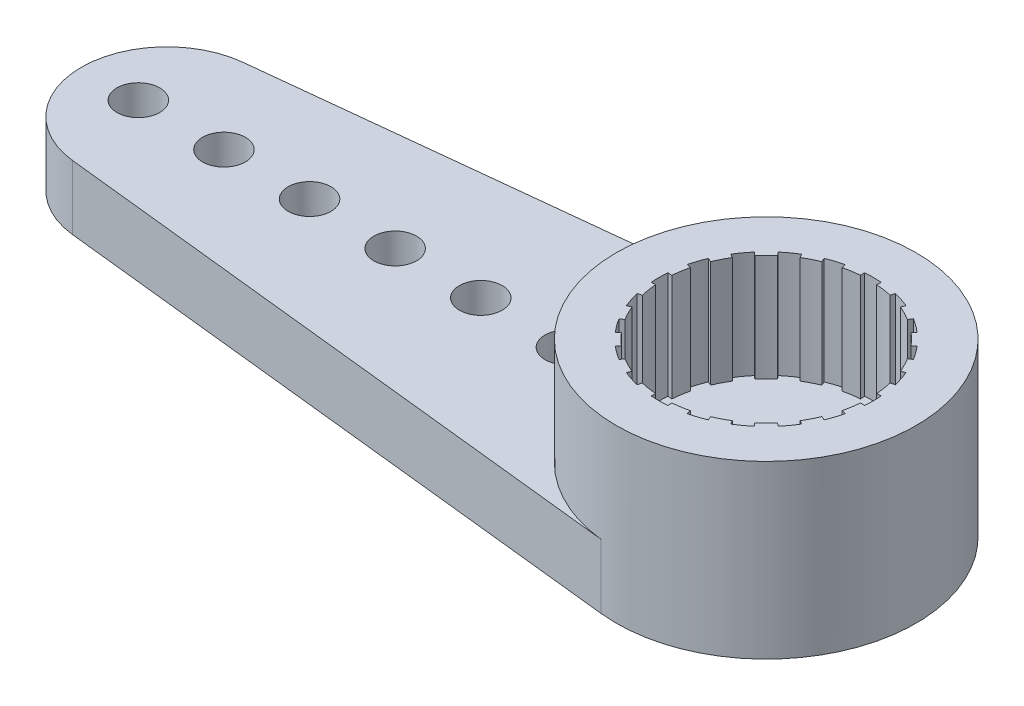
SolidWorks part; units mm, degrees
ref_plane "Front Plane" through (0, 0, 0) normal (0, 0, 1) x (1, 0, 0)
ref_plane "Top Plane" through (0, 0, 0) normal (0, 1, 0) x (1, 0, 0)
ref_plane "Right Plane" through (0, 0, 0) normal (1, 0, 0) x (0, 0, -1)
sketch "Sketch1" plane through (0, 0, 0) normal (0, 1, 0) x (1, 0, 0)
  line L0 (0, 0) -> (2.5, 0) construction
  line L1 (0, 0) -> (2.3705, 0.3754) construction
  line L2 (0, 0) -> (2.4923, 0.1961) construction
  line L3 (2.3926, 0.1883) -> (2.4923, 0.1961)
  line L4 (2.3926, -0.1883) -> (2.4923, -0.1961)
  line L5 (2.3337, -0.5603) -> (2.4309, -0.5836)
  line L6 (2.2173, -0.9184) -> (2.3097, -0.9567)
  line L7 (2.0463, -1.254) -> (2.1316, -1.3062)
  line L8 (1.825, -1.5587) -> (1.901, -1.6236)
  line L9 (1.5587, -1.825) -> (1.6236, -1.901)
  line L10 (1.254, -2.0463) -> (1.3062, -2.1316)
  line L11 (0.9184, -2.2173) -> (0.9567, -2.3097)
  line L12 (0.5603, -2.3337) -> (0.5836, -2.4309)
  line L13 (0.1883, -2.3926) -> (0.1961, -2.4923)
  line L14 (-0.1883, -2.3926) -> (-0.1961, -2.4923)
  line L15 (-0.5603, -2.3337) -> (-0.5836, -2.4309)
  line L16 (-0.9184, -2.2173) -> (-0.9567, -2.3097)
  line L17 (-1.254, -2.0463) -> (-1.3062, -2.1316)
  line L18 (-1.5587, -1.825) -> (-1.6236, -1.901)
  line L19 (-1.825, -1.5587) -> (-1.901, -1.6236)
  line L20 (-2.0463, -1.254) -> (-2.1316, -1.3062)
  line L21 (-2.2173, -0.9184) -> (-2.3097, -0.9567)
  line L22 (-2.3337, -0.5603) -> (-2.4309, -0.5836)
  line L23 (-2.3926, -0.1883) -> (-2.4923, -0.1961)
  line L24 (-2.3926, 0.1883) -> (-2.4923, 0.1961)
  line L25 (-2.3337, 0.5603) -> (-2.4309, 0.5836)
  line L26 (-2.2173, 0.9184) -> (-2.3097, 0.9567)
  line L27 (-2.0463, 1.254) -> (-2.1316, 1.3062)
  line L28 (-1.825, 1.5587) -> (-1.901, 1.6236)
  line L29 (-1.5587, 1.825) -> (-1.6236, 1.901)
  line L30 (-1.254, 2.0463) -> (-1.3062, 2.1316)
  line L31 (-0.9184, 2.2173) -> (-0.9567, 2.3097)
  line L32 (-0.5603, 2.3337) -> (-0.5836, 2.4309)
  line L33 (-0.1883, 2.3926) -> (-0.1961, 2.4923)
  line L34 (0.1883, 2.3926) -> (0.1961, 2.4923)
  line L35 (0.5603, 2.3337) -> (0.5836, 2.4309)
  line L36 (0.9184, 2.2173) -> (0.9567, 2.3097)
  line L37 (1.254, 2.0463) -> (1.3062, 2.1316)
  line L38 (1.5587, 1.825) -> (1.6236, 1.901)
  line L39 (1.825, 1.5587) -> (1.901, 1.6236)
  line L40 (2.0463, 1.254) -> (2.1316, 1.3062)
  line L41 (2.2173, 0.9184) -> (2.3097, 0.9567)
  line L42 (2.3337, 0.5603) -> (2.4309, 0.5836)
  circle A0 centre (0, 0) radius 2.5 construction
  circle A1 centre (0, 0) radius 2.4 construction
  circle A2 centre (0, 0) radius 3.5
  arc A3 (2.3705, 0.3754) -> (2.3926, 0.1883) centre (0, 0) cw
  arc A4 (2.4923, 0.1961) -> (2.4923, -0.1961) centre (0, 0) cw
  arc A5 (2.3705, -0.3754) -> (2.3926, -0.1883) centre (0, 0) ccw
  arc A6 (2.3705, -0.3754) -> (2.3337, -0.5603) centre (0, 0) cw
  arc A7 (2.4309, -0.5836) -> (2.3097, -0.9567) centre (0, 0) cw
  arc A8 (2.1384, -1.0896) -> (2.2173, -0.9184) centre (0, 0) ccw
  arc A9 (2.1384, -1.0896) -> (2.0463, -1.254) centre (0, 0) cw
  arc A10 (2.1316, -1.3062) -> (1.901, -1.6236) centre (0, 0) cw
  arc A11 (1.6971, -1.6971) -> (1.825, -1.5587) centre (0, 0) ccw
  arc A12 (1.6971, -1.6971) -> (1.5587, -1.825) centre (0, 0) cw
  arc A13 (1.6236, -1.901) -> (1.3062, -2.1316) centre (0, 0) cw
  arc A14 (1.0896, -2.1384) -> (1.254, -2.0463) centre (0, 0) ccw
  arc A15 (1.0896, -2.1384) -> (0.9184, -2.2173) centre (0, 0) cw
  arc A16 (0.9567, -2.3097) -> (0.5836, -2.4309) centre (0, 0) cw
  arc A17 (0.3754, -2.3705) -> (0.5603, -2.3337) centre (0, 0) ccw
  arc A18 (0.3754, -2.3705) -> (0.1883, -2.3926) centre (0, 0) cw
  arc A19 (0.1961, -2.4923) -> (-0.1961, -2.4923) centre (0, 0) cw
  arc A20 (-0.3754, -2.3705) -> (-0.1883, -2.3926) centre (0, 0) ccw
  arc A21 (-0.3754, -2.3705) -> (-0.5603, -2.3337) centre (0, 0) cw
  arc A22 (-0.5836, -2.4309) -> (-0.9567, -2.3097) centre (0, 0) cw
  arc A23 (-1.0896, -2.1384) -> (-0.9184, -2.2173) centre (0, 0) ccw
  arc A24 (-1.0896, -2.1384) -> (-1.254, -2.0463) centre (0, 0) cw
  arc A25 (-1.3062, -2.1316) -> (-1.6236, -1.901) centre (0, 0) cw
  arc A26 (-1.6971, -1.6971) -> (-1.5587, -1.825) centre (0, 0) ccw
  arc A27 (-1.6971, -1.6971) -> (-1.825, -1.5587) centre (0, 0) cw
  arc A28 (-1.901, -1.6236) -> (-2.1316, -1.3062) centre (0, 0) cw
  arc A29 (-2.1384, -1.0896) -> (-2.0463, -1.254) centre (0, 0) ccw
  arc A30 (-2.1384, -1.0896) -> (-2.2173, -0.9184) centre (0, 0) cw
  arc A31 (-2.3097, -0.9567) -> (-2.4309, -0.5836) centre (0, 0) cw
  arc A32 (-2.3705, -0.3754) -> (-2.3337, -0.5603) centre (0, 0) ccw
  arc A33 (-2.3705, -0.3754) -> (-2.3926, -0.1883) centre (0, 0) cw
  arc A34 (-2.4923, -0.1961) -> (-2.4923, 0.1961) centre (0, 0) cw
  arc A35 (-2.3705, 0.3754) -> (-2.3926, 0.1883) centre (0, 0) ccw
  arc A36 (-2.3705, 0.3754) -> (-2.3337, 0.5603) centre (0, 0) cw
  arc A37 (-2.4309, 0.5836) -> (-2.3097, 0.9567) centre (0, 0) cw
  arc A38 (-2.1384, 1.0896) -> (-2.2173, 0.9184) centre (0, 0) ccw
  arc A39 (-2.1384, 1.0896) -> (-2.0463, 1.254) centre (0, 0) cw
  arc A40 (-2.1316, 1.3062) -> (-1.901, 1.6236) centre (0, 0) cw
  arc A41 (-1.6971, 1.6971) -> (-1.825, 1.5587) centre (0, 0) ccw
  arc A42 (-1.6971, 1.6971) -> (-1.5587, 1.825) centre (0, 0) cw
  arc A43 (-1.6236, 1.901) -> (-1.3062, 2.1316) centre (0, 0) cw
  arc A44 (-1.0896, 2.1384) -> (-1.254, 2.0463) centre (0, 0) ccw
  arc A45 (-1.0896, 2.1384) -> (-0.9184, 2.2173) centre (0, 0) cw
  arc A46 (-0.9567, 2.3097) -> (-0.5836, 2.4309) centre (0, 0) cw
  arc A47 (-0.3754, 2.3705) -> (-0.5603, 2.3337) centre (0, 0) ccw
  arc A48 (-0.3754, 2.3705) -> (-0.1883, 2.3926) centre (0, 0) cw
  arc A49 (-0.1961, 2.4923) -> (0.1961, 2.4923) centre (0, 0) cw
  arc A50 (0.3754, 2.3705) -> (0.1883, 2.3926) centre (0, 0) ccw
  arc A51 (0.3754, 2.3705) -> (0.5603, 2.3337) centre (0, 0) cw
  arc A52 (0.5836, 2.4309) -> (0.9567, 2.3097) centre (0, 0) cw
  arc A53 (1.0896, 2.1384) -> (0.9184, 2.2173) centre (0, 0) ccw
  arc A54 (1.0896, 2.1384) -> (1.254, 2.0463) centre (0, 0) cw
  arc A55 (1.3062, 2.1316) -> (1.6236, 1.901) centre (0, 0) cw
  arc A56 (1.6971, 1.6971) -> (1.5587, 1.825) centre (0, 0) ccw
  arc A57 (1.6971, 1.6971) -> (1.825, 1.5587) centre (0, 0) cw
  arc A58 (1.901, 1.6236) -> (2.1316, 1.3062) centre (0, 0) cw
  arc A59 (2.1384, 1.0896) -> (2.0463, 1.254) centre (0, 0) ccw
  arc A60 (2.1384, 1.0896) -> (2.2173, 0.9184) centre (0, 0) cw
  arc A61 (2.3097, 0.9567) -> (2.4309, 0.5836) centre (0, 0) cw
  arc A62 (2.3705, 0.3754) -> (2.3337, 0.5603) centre (0, 0) ccw
  point P130 (0, 0)
  dimension "D1" = 5
  dimension "D2" = 4.8
  dimension "D3" = 7
  dimension "D4" = 9
  dimension "D5" = 4.5
  dimension "D6" = 20
extrude "Boss-Extrude1" add sketch "Sketch1" along normal blind 4
sketch "Sketch2" plane through (0, 0, 0) normal (0, -1, 0) x (1, 0, 0)
  line L0 (0, 0) -> (-16, 0) construction
  line L1 (-14.2143, 1.9885) -> (-0.375, 3.4799)
  line L2 (-14.2143, -1.9885) -> (-0.375, -3.4799)
  arc A0 (-0.375, -3.4799) -> (-0.375, 3.4799) centre (0, 0) ccw
  circle A1 centre (0, 0) radius 1
  arc A2 (-14.2143, 1.9885) -> (-14.2143, -1.9885) centre (-14, 0) ccw
  circle A3 centre (-14.6676, 0) radius 0.5
  circle A4 centre (-12.6676, 0) radius 0.5
  circle A5 centre (-10.6676, 0) radius 0.5
  circle A6 centre (-8.6676, 0) radius 0.5
  circle A7 centre (-6.6676, 0) radius 0.5
  circle A8 centre (-4.6676, 0) radius 0.5
  dimension "D1" = 7
  dimension "D2" = 2
  dimension "D3" = 4
  dimension "D4" = 1
  dimension "D5" = 6
extrude "Boss-Extrude2" add sketch "Sketch2" against normal blind 1.5
sketch "Sketch3" plane through (0, 0, 0) normal (0, -1, 0) x (-1, 0, 0)
  circle A0 centre (0, 0) radius 2.25
  dimension "D1" = 4.5
extrude "Cut-Extrude1" cut sketch "Sketch3" against normal blind 1
